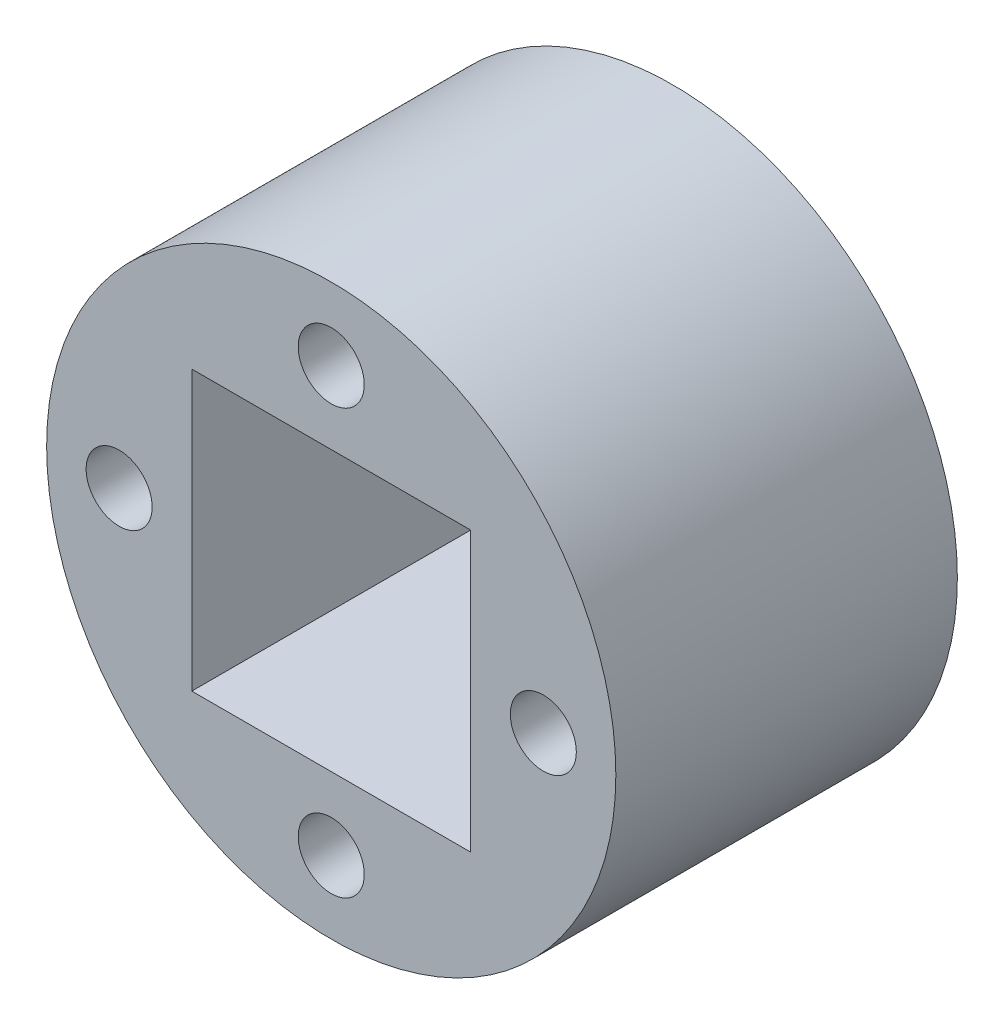
SolidWorks part; units mm, degrees
ref_plane "Front Plane" through (0, 0, 0) normal (0, 0, 1) x (1, 0, 0)
ref_plane "Top Plane" through (0, 0, 0) normal (0, 1, 0) x (1, 0, 0)
ref_plane "Right Plane" through (0, 0, 0) normal (1, 0, 0) x (0, 0, -1)
sketch "Sketch1" plane through (0, 0, 0) normal (0, 0, 1) x (1, 0, 0)
  circle A0 centre (0, 0) radius 12.5
  dimension "D2" = 25
extrude "Boss-Extrude1" add sketch "Sketch1" along normal mid plane 15
sketch "Sketch8" plane through (0, 0, 7.5) normal (0, 0, 1) x (1, 0, 0)
  line L2 (-6.125, 6.125) -> (6.125, 6.125)
  line L3 (-6.125, 6.125) -> (-6.125, -6.125)
  line L4 (-6.125, -6.125) -> (6.125, -6.125)
  line L5 (6.125, 6.125) -> (6.125, -6.125)
  line L6 (-6.125, 6.125) -> (6.125, -6.125) construction
  line L7 (-6.125, -6.125) -> (6.125, 6.125) construction
  point P5 (0, 0)
  point P14 (0, 0)
  dimension "D1" = 12.25
extrude "Cut-Extrude1" cut sketch "Sketch8" against normal up to next
sketch "Sketch11" plane through (0, 0, 7.5) normal (0, 0, 1) x (1, 0, 0)
  line L0 (6.125, -6.125) -> (6.125, 6.125) construction
  circle A0 centre (9.315, 0) radius 1.45
  circle A1 centre (0, -9.315) radius 1.45
  circle A2 centre (-9.315, 0) radius 1.45
  circle A3 centre (0, 9.315) radius 1.45
  point P13 (0, 0)
  dimension "D1" = 2.9
  dimension "D2" = 3.19
  dimension "D3" = 4
extrude "Cut-Extrude4" cut sketch "Sketch11" against normal up to next
equation "\"drumDiameter\"= 25"
equation "\"drumLength\"=15"
equation "\"foamThickness\"= 5"
equation "\"drumAbove\"= 0.6"
equation "\"holderThicc\"= 2"
equation "\"D1@Boss-Extrude1\"=\"drumLength\""
equation "\"squareBarLength\"= 12.25"
equation "\"D1@Sketch8\"=\"squareBarLength\""
equation "\"toothlen\"= 2.5"
